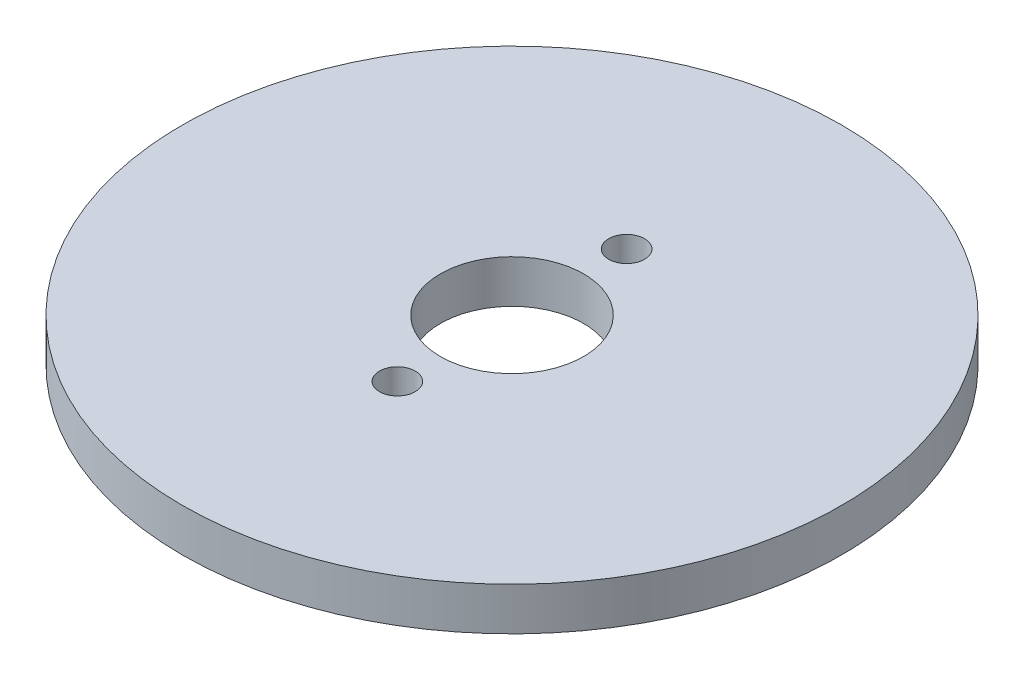
SolidWorks part; units mm, degrees
ref_plane "Front" through (0, 0, 0) normal (0, 0, 1) x (1, 0, 0)
ref_plane "Top" through (0, 0, 0) normal (0, 1, 0) x (1, 0, 0)
ref_plane "Right" through (0, 0, 0) normal (1, 0, 0) x (0, 0, -1)
sketch "Sketch1" plane through (0, 0, 0) normal (0, 1, 0) x (1, 0, 0)
  circle A0 centre (0, 0) radius 23
  dimension "D1" = 46
extrude "Boss-Extrude1" add sketch "Sketch1" along normal blind 3
sketch "Sketch2" plane through (0, 3, 0) normal (0, 1, 0) x (1, 0, 0)
  circle A0 centre (0, 0) radius 5
  dimension "D1" = 10
extrude "Cut-Extrude1" cut sketch "Sketch2" against normal through all
sketch "Sketch3" plane through (0, 3, 0) normal (0, 1, 0) x (1, 0, 0)
  line L0 (0, 0) -> (0, 8)
  line L1 (0, 0) -> (0, -8)
  circle A0 centre (0, 8) radius 1.25
  circle A1 centre (0, -8) radius 1.25
  dimension "D2" = 2.5
  dimension "D4" = 2.5
  dimension "D1" = 8
  dimension "D3" = 8
extrude "Cut-Extrude2" cut sketch "Sketch3" against normal through all
